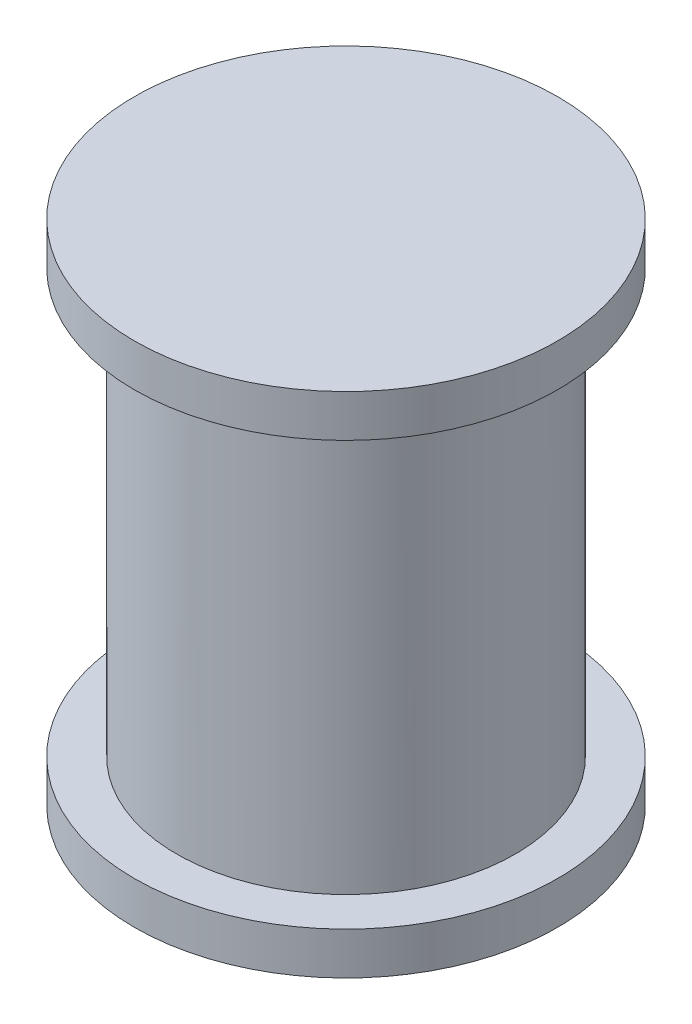
SolidWorks part; units mm, degrees
ref_plane "Alzado" through (0, 0, 0) normal (0, 0, 1) x (1, 0, 0)
ref_plane "Planta" through (0, 0, 0) normal (0, 1, 0) x (1, 0, 0)
ref_plane "Vista lateral" through (0, 0, 0) normal (1, 0, 0) x (0, 0, -1)
sketch "Croquis1" plane through (0, 0, 0) normal (0, 1, 0) x (1, 0, 0)
  circle A0 centre (0, 0) radius 4
extrude "Saliente-Extruir1" add sketch "Croquis1" along normal blind 10
sketch "Croquis2" plane through (0, 10, 0) normal (0, 1, 0) x (1, 0, 0)
  circle A0 centre (0, 0) radius 5
extrude "Saliente-Extruir2" add sketch "Croquis2" along normal blind 1
sketch "Croquis3" plane through (0, 0, 0) normal (0, -1, 0) x (1, 0, 0)
  circle A0 centre (0, 0) radius 5
extrude "Saliente-Extruir3" add sketch "Croquis3" along normal blind 1
